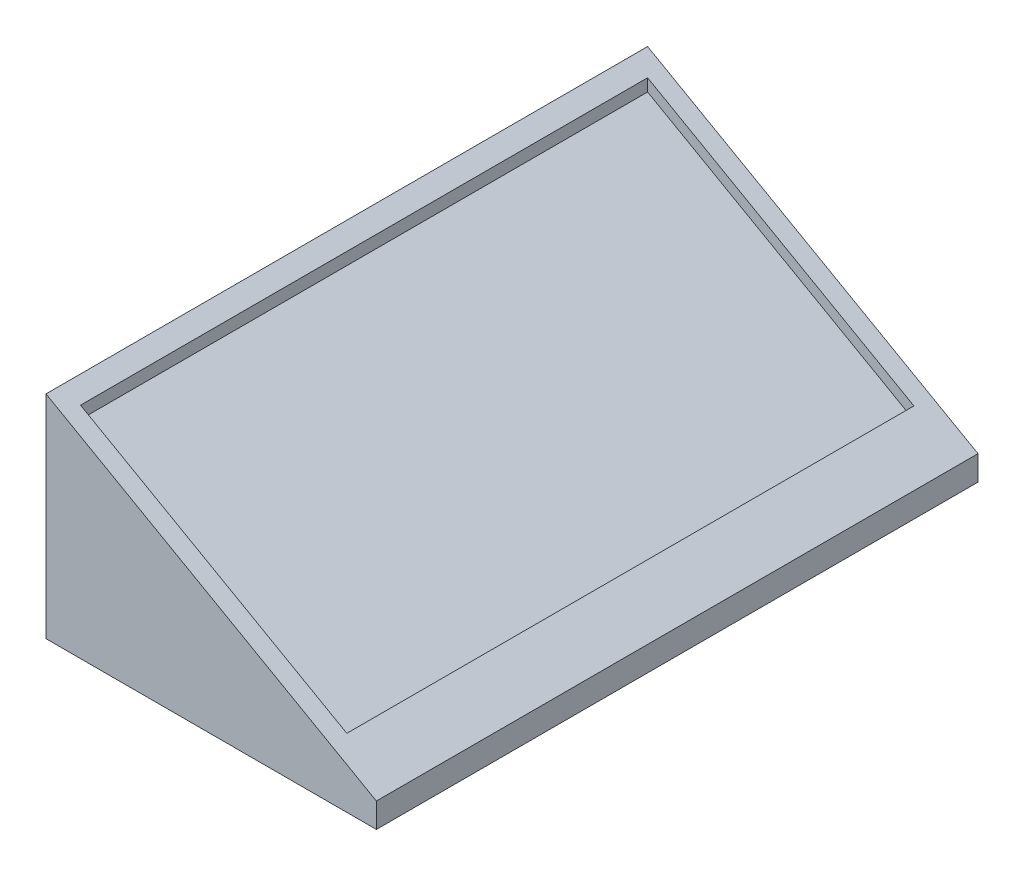
SolidWorks part; units mm, degrees
ref_plane "Front Plane" through (0, 0, 0) normal (0, 0, 1) x (1, 0, 0)
ref_plane "Top Plane" through (0, 0, 0) normal (0, 1, 0) x (1, 0, 0)
ref_plane "Right Plane" through (0, 0, 0) normal (1, 0, 0) x (0, 0, -1)
sketch "Sketch1" plane through (0, 0, 0) normal (0, 0, 1) x (1, 0, 0)
  line L0 (0, 0) -> (67, 0)
  line L1 (67, 0) -> (0, 38)
  line L2 (0, 38) -> (0, 0)
  dimension "D1" = 38
  dimension "D2" = 67
extrude "Boss-Extrude1" add sketch "Sketch1" along normal blind 122
sketch "Sketch3" plane through (0, 0, 0) normal (0, -1, 0) x (1, 0, 0)
  line L0 (67, 122) -> (67, 0) construction
  line L1 (63.5395, 3.5) -> (3.5, 3.5)
  line L2 (63.5395, 3.5) -> (63.5395, 118.5)
  line L3 (63.5395, 118.5) -> (3.5, 118.5)
  line L4 (3.5, 3.5) -> (3.5, 118.5)
  line L5 (0, 122) -> (0, 0) construction
  line L6 (0, 122) -> (67, 122) construction
  line L7 (0, 0) -> (67, 0) construction
  dimension "D1" = 3.4605
  dimension "D2" = 3.5
  dimension "D3" = 3.5
  dimension "D4" = 3.5
extrude "Cut-Extrude1" cut sketch "Sketch3" against normal blind 122
sketch "Sketch4" plane through (0, 0, 118.5) normal (0, 0, -1) x (-1, 0, 0)
  line L0 (-3.5, 33.5149) -> (-3.5, 30.6408)
  line L1 (-3.5, 33.5149) -> (-57.4299, 2.9278)
  line L2 (-3.5, 30.6408) -> (-57.4299, 0.0537)
  line L3 (-57.4299, 2.9278) -> (-57.4299, 0.0537)
  line L4 (-3.5, 36.0149) -> (-3.5, 0) construction
  line L5 (-63.5395, 1.9627) -> (-3.5, 36.0149) construction
  dimension "D1" = 2.5
  dimension "D2" = 180
  dimension "D3" = 2.5
  dimension "D4" = 62
extrude "Boss-Extrude3" add sketch "Sketch4" along normal blind 116.5
sketch "Sketch6" plane through (0, 0, 118.5) normal (0, 0, -1) x (-1, 0, 0)
  line L0 (-57.4299, 2.9278) -> (-58.5027, 4.8194)
  line L1 (-63.5395, 1.9627) -> (-3.5, 36.0149) construction
  line L2 (-58.5027, 4.8194) -> (-63.5395, 1.9627)
  line L3 (-63.5395, 1.9627) -> (-63.5395, 0)
  line L4 (-63.5395, 0) -> (-57.4299, 0.0537)
  line L5 (-57.4299, 0.0537) -> (-57.4299, 2.9278)
extrude "Boss-Extrude4" add sketch "Sketch6" along normal blind 116.5
sketch "Sketch9" plane through (0, 0, 3.5) normal (0, 0, 1) x (1, 0, 0)
  line L0 (58.5027, 4.8194) -> (57.5027, 5.3865)
  line L1 (3.5, 36.0149) -> (58.5027, 4.8194) construction
  line L2 (57.5027, 5.3865) -> (56.4299, 3.495)
  line L3 (57.4299, 2.9278) -> (3.5, 33.5149) construction
  line L4 (56.4299, 3.495) -> (57.4299, 2.9278)
  line L5 (57.4299, 2.9278) -> (58.5027, 4.8194)
  dimension "D1" = 1
extrude "Boss-Extrude5" add sketch "Sketch9" along normal blind 116.5
sketch "Sketch10" plane through (0, 0, 0) normal (0, -1, 0) x (1, 0, 0)
  line L0 (0, 122) -> (67, 122) construction
  line L1 (0, 0) -> (2, 0)
  line L2 (0, 0) -> (0, 122)
  line L3 (0, 122) -> (2, 122)
  line L4 (2, 0) -> (2, 122)
  line L6 (67, 122) -> (2, 122)
  line L7 (67, 122) -> (67, 120)
  line L8 (67, 120) -> (2, 120)
  line L9 (2, 122) -> (2, 120)
  line L10 (67, 0) -> (65, 0)
  line L11 (67, 0) -> (67, 120)
  line L12 (67, 120) -> (65, 120)
  line L14 (65, 0) -> (2, 0)
  line L15 (65, 0) -> (65, 2)
  line L16 (65, 2) -> (2, 2)
  line L17 (2, 0) -> (2, 2)
  line L18 (67, 120) -> (65, 120)
  line L19 (67, 120) -> (67, 0)
  line L20 (67, 0) -> (65, 0)
  line L21 (65, 120) -> (65, 0)
  line M13 (0, 0) -> (67, 0)
  line M14 (67, 0) -> (67, 122)
  line M15 (67, 122) -> (0, 122)
  line M16 (0, 122) -> (0, 0)
  dimension "D1" = 2
  dimension "D2" = 2
  dimension "D3" = 2
  dimension "D4" = 2
extrude "Boss-Extrude6" add sketch "Sketch10" along normal blind 5 contours L4 M13 M15 M16 | L8 L4 M14 M15 | L15 L16 L4 M13 | L8 L21 L15 M13 M14
